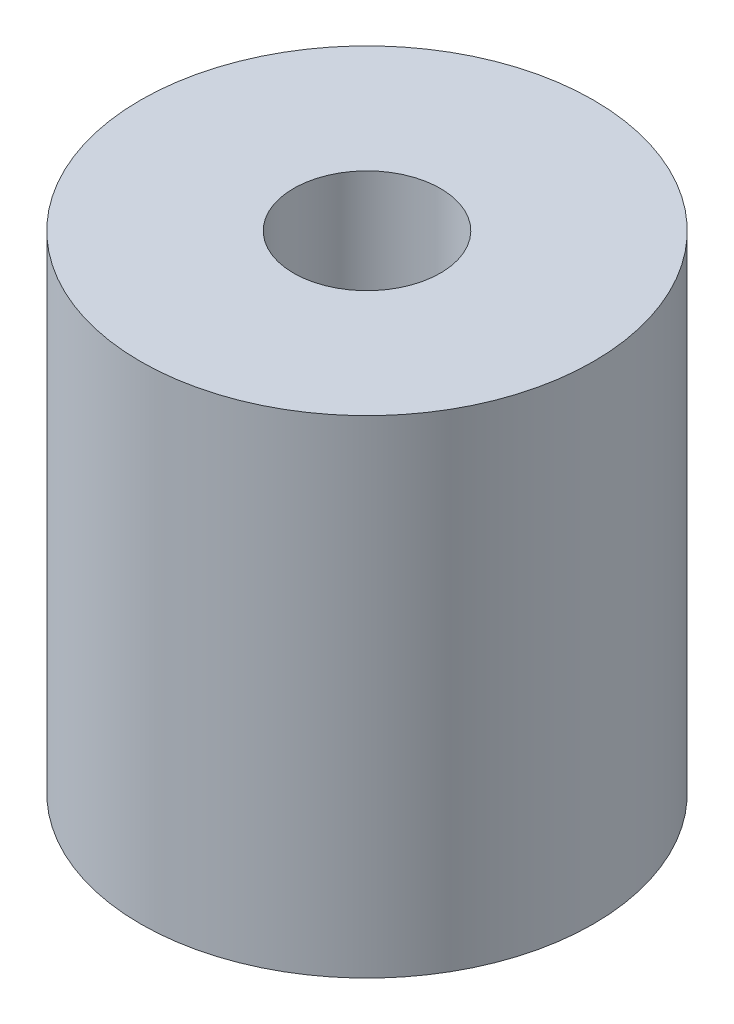
SolidWorks part; units mm, degrees
material "Custom Plastic"
ref_plane "X-Y Datum" through (0, 0, 0) normal (0, 0, 1) x (1, 0, 0)
ref_plane "X-Z Datum" through (0, 0, 0) normal (0, 1, 0) x (1, 0, 0)
ref_plane "Y-Z Datum" through (0, 0, 0) normal (1, 0, 0) x (0, 0, -1)
sketch "Sketch1" plane through (0, 0, 0) normal (0, 1, 0) x (1, 0, 0)
  circle A0 centre (0, 0) radius 3.302
  circle A1 centre (0, 0) radius 10.1854
  dimension "D1" = 20.3708
  dimension "D2" = 6.604
extrude "Boss-Extrude1" add sketch "Sketch1" against normal blind 21.9075
